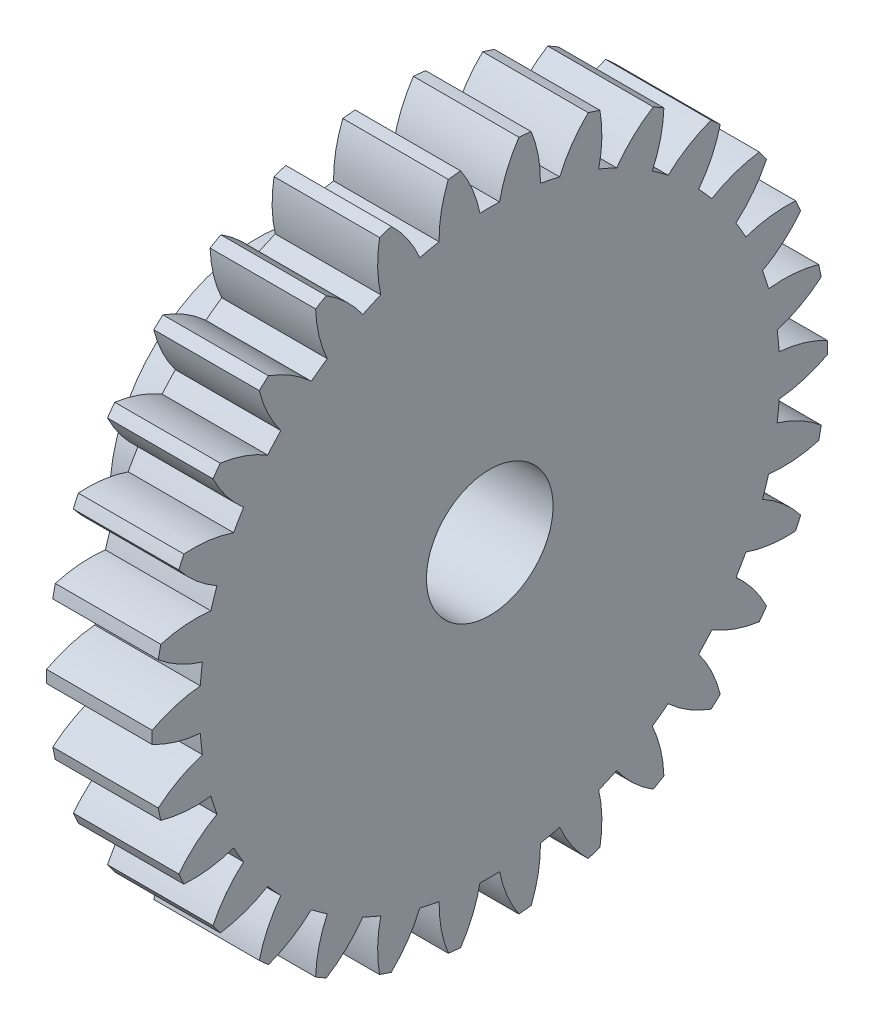
SolidWorks part; units mm, degrees
ref_plane "Plane1" through (0, 0, 0) normal (0, 0, 1) x (1, 0, 0)
ref_plane "Plane2" through (0, 0, 0) normal (0, 1, 0) x (1, 0, 0)
ref_plane "Plane3" through (0, 0, 0) normal (1, 0, 0) x (0, 0, -1)
sketch "HoldingSke" plane through (0, 0, 0) normal (0, 1, 0) x (1, 0, 0)
  line L0 (0, 0) -> (0.866, -0.5)
  line L1 (-15, 0) -> (100, 0) construction
  line L2 (0, 0) -> (-2.1039, 2.3779)
  line L3 (0, 0) -> (-11.863, 4.5341)
  line L4 (0, 0) -> (7.479, 4.318)
  line L5 (0, 0) -> (-10.3065, -3.844)
  line L6 (0, 0) -> (-4.1448, -2.7965)
  line L7 (-2.1039, 2.3779) -> (0.2639, 13.1201)
  line L8 (-76.2, 54.61) -> (-75.2, 54.61)
  line L9 (-71.009, 38.7566) -> (-53.1078, 45.2721)
  line L10 (-76.2, 71.12) -> (104.1128, 71.12)
  line L11 (0, 0) -> (-5, 0)
  line L12 (-76.2, 101.6) -> (-76.162, 101.6)
  line L13 (24.9733, 27.94) -> (52.9518, 28.4284)
  line L14 (24.9733, 27.94) -> (24.9743, 27.94)
  line L15 (24.9733, 27.94) -> (100.4006, 29.5858)
  line L16 (-63.627, -1) -> (-12.827, -1)
  circle A0 centre (0, 0) radius 3
  circle A1 centre (0, 0) radius 7
  circle A2 centre (0, 0) radius 7
  circle A3 centre (0, 0) radius 3
  dimension "Pitch" = 1
  dimension "Ap" = 20
  dimension "H" = 19.05
  dimension "Pitch_radius" = 180.3128
  dimension "Backlash" = 0.038
  dimension "Addendum_fac" = 1
  dimension "Dedendum_fac" = 1.25
  dimension "Clearance_fac" = 0.25
  dimension "Dedendum_add" = 0.001
  dimension "Module" = 1
sketch "BasProSke" plane through (0, 0, 0) normal (0, 1, 0) x (1, 0, 0)
  line L0 (-10, 0) -> (60, 0) construction
  line L1 (0, 0) -> (0, 16)
  line L2 (0, 0) -> (5, 0)
  line L3 (5, 0) -> (5, 16)
  line L4 (5, 16) -> (0, 16)
revolve "Base-Revolve" add sketch "BasProSke" angle 360 about L0
sketch "TooCutSke" plane through (0, 0, 0) normal (1, 0, 0) x (0, 0, -1)
  line L1 (0, 0) -> (0, 107) construction
  line L2 (0, 0) -> (-0.8515, 14.9758) construction
  line L3 (0, 0) -> (-3.1323, 29.8014) construction
  line L4 (-0.8515, 14.9758) -> (-1.5661, 14.9007) construction
  arc A0 (0.4664, 13.7411) -> (-0.4664, 13.7411) centre (0, 0) ccw
  arc A1 (1.3975, 15.9644) -> (-1.3975, 15.9644) centre (0, 0) ccw
  circle A2 centre (0, 0) radius 15 construction
  circle A3 centre (0, 0) radius 14.0954 construction
  arc A4 (-0.4664, 13.7411) -> (-1.3975, 15.9644) centre (-6.3534, 12.5823) ccw
  arc A5 (1.3975, 15.9644) -> (0.4664, 13.7411) centre (6.3534, 12.5823) ccw
  dimension "Half_CT" = 0.7185
extrude "ToothCut" cut sketch "TooCutSke" along normal through all
fillet "Breaks" [suppressed] radius 0.02
fillet "RootFillets" [suppressed] radius 0.251
pattern_circular "TeethCuts" count 30 every 12 about axis through (-10, 0, 0) along (1, 0, 0) of "ToothCut", "RootFillets", "Breaks"
sketch "HubNeaOneSke" plane through (0, 0, 0) normal (-1, 0, 0) x (0, 0, 1)
  circle A0 centre (0, 0) radius 7
extrude "HubNearOne" add sketch "HubNeaOneSke" along normal blind 6.0001
sketch "HubNeaBotSke" plane through (0, 0, 0) normal (-1, 0, 0) x (0, 0, 1)
  circle A0 centre (0, 0) radius 7
extrude "HubNearBoth" [suppressed] add sketch "HubNeaBotSke" along normal blind 3
ref_plane "FarPln" through (5, 0, 0) normal (1, 0, 0) x (0, 0, -1)
sketch "HubFarSke" plane through (5, 0, 0) normal (1, 0, 0) x (0, 0, -1)
  circle A0 centre (0, 0) radius 7
extrude "HubFar" [suppressed] add sketch "HubFarSke" along normal blind 3
sketch "BorSke" plane through (0, 0, 0) normal (1, 0, 0) x (0, 0, -1)
  circle A0 centre (0, 0) radius 3
extrude "Bore" cut sketch "BorSke" along normal mid plane 22.0001
sketch "KeySke" plane through (0, 0, 0) normal (1, 0, 0) x (0, 0, -1)
  line L0 (-1, 0) -> (-1, 4)
  line L1 (-1, 4) -> (1, 4)
  line L2 (1, 4) -> (1, 0)
  line L3 (0, 0) -> (0, 34) construction
  line L4 (-1, 0) -> (1, 0)
extrude "Keyway" [suppressed] cut sketch "KeySke" along normal mid plane 22.0001
pattern_circular "Keyway2" [suppressed] count 2 every 90 about axis through (-10, 0, 0) along (1, 0, 0)
equation "' \"Module@HoldingSke\" = 6.35"
equation "' \"Num_teeth@HoldingSke\" = 12"
equation "' \"Ap@HoldingSke\" =  20"
equation "' \"Ap@HoldingSke\" = 20"
equation "' \"Width@HoldingSke\" = 0.5 * 25.4"
equation "' \"Hub_dia@HoldingSke\"= 1 * 25.4"
equation "' \"Hub_dia@HoldingSke\" = 1 * 25.4"
equation "' \"Overall_len@HoldingSke\" = 1.0 * 25.4"
equation "' \"Bore@HoldingSke\" = 0.75 * 25.4"
equation "' \"T_dim@HoldingSke\" = 0.1 * 25.4"
equation "' \"Width@KeySke\" = 0.25 * 25.4"
equation "' \"Show_teeth@HoldingSke\" = 13"
equation "' \"Backlash@HoldingSke\" = 0.009 * 25.4"
equation "' \"Addendum_fac@HoldingSke\" = 1.0"
equation "' \"Dedendum_fac@HoldingSke\" = 1.25"
equation "' \"Dedendum_add@HoldingSke\" = 0.00005 * 25.4"
equation "' \"Clearance_fac@HoldingSke\" = 0.25"
equation "\"Pitch@HoldingSke\" = 1 / \"Module@HoldingSke\""
equation "\"Overcut_dia@TooCutSke\" = (\"Num_teeth@HoldingSke\" + 2 * \"Addendum_fac@HoldingSke\") / \"Pitch@HoldingSke\" + 0.002 * 25.4"
equation "\"Pitch_dia@TooCutSke\" = \"Num_teeth@HoldingSke\" / \"Pitch@HoldingSke\""
equation "\"Base_dia@TooCutSke\" = \"Num_teeth@HoldingSke\" / \"Pitch@HoldingSke\" * cos((\"Ap@HoldingSke\"  * 3.14159265 / 180))"
equation "\"Root_dia@TooCutSke\" = (\"Num_teeth@HoldingSke\" + 2) / \"Pitch@HoldingSke\" - 2 * (\"Addendum_fac@HoldingSke\" + \"Dedendum_fac@HoldingSke\") / \"Pitch@HoldingSke\" - \"Dedendum_add@HoldingSke\" * 2"
equation "\"Half_ang@TooCutSke\" = 180 / \"Num_teeth@HoldingSke\""
equation "\"Half_CT@TooCutSke\" = \"Num_teeth@HoldingSke\" / \"Pitch@HoldingSke\" * sin((3.14159265 / 2 / \"Num_teeth@HoldingSke\")) / 2 - 7 * \"Backlash@HoldingSke\" / 4"
equation "\"Flank_rad@TooCutSke\" = \"Num_teeth@HoldingSke\" / \"Pitch@HoldingSke\" / 5"
equation "\"Radius@RootFillets\" = \"Clearance_fac@HoldingSke\" / \"Pitch@HoldingSke\" + \"Dedendum_add@HoldingSke\""
equation "\"Break_rad@Breaks\" = 0.02 / \"Pitch@HoldingSke\""
equation "\"Thickness@HoldingSke\" = \"Width@HoldingSke\""
equation "\"OAL@HoldingSke\" = \"Thickness@HoldingSke\""
equation "\"MHD@HoldingSke\" = (\"Num_teeth@HoldingSke\" + 2) / \"Pitch@HoldingSke\" - 2 * (\"Addendum_fac@HoldingSke\" + \"Dedendum_fac@HoldingSke\")  / \"Pitch@HoldingSke\" - \"Dedendum_add@HoldingSke\" * 2"
equation "\"MBD@HoldingSke\" = (\"Num_teeth@HoldingSke\" + 2) / \"Pitch@HoldingSke\" - 2 * (\"Addendum_fac@HoldingSke\" + \"Dedendum_fac@HoldingSke\")  / \"Pitch@HoldingSke\" - \"Dedendum_add@HoldingSke\" * 2 - 0.002 * 25.4"
equation "\"MHD@HoldingSke\" = ((sgn( \"MHD@HoldingSke\" - \"Hub_dia@HoldingSke\" )-1)*( \"MHD@HoldingSke\" - \"Hub_dia@HoldingSke\" ))/-2+ \"Hub_dia@HoldingSke\""
equation "\"MBD@HoldingSke\" = ((sgn( \"MBD@HoldingSke\" - \"Bore@HoldingSke\" )-1)*( \"MBD@HoldingSke\" - \"Bore@HoldingSke\" ))/-2+ \"Bore@HoldingSke\""
equation "\"OAL@HoldingSke\" = ((sgn( \"OAL@HoldingSke\" - \"Overall_len@HoldingSke\" )+1)*( \"OAL@HoldingSke\" - \"Overall_len@HoldingSke\" ))/2 + \"Overall_len@HoldingSke\" + 0.000002 * 25.4"
equation "\"Num_teeth@TeethCuts\" = int( \"Show_teeth@HoldingSke\" ) + 1"
equation "\"Num_teeth@TeethCuts\" = ((sgn( \"Num_teeth@TeethCuts\" - \"Num_teeth@HoldingSke\" )-1)*( \"Num_teeth@TeethCuts\" - \"Num_teeth@HoldingSke\" ))/-2+ \"Num_teeth@HoldingSke\""
equation "\"Num_teeth@TeethCuts\" = ((sgn( \"Num_teeth@TeethCuts\" - 2.0)+1)*( \"Num_teeth@TeethCuts\" - 2.0))/2 +2.0"
equation "\"Angle@TeethCuts\" = 360.0 / \"Num_teeth@HoldingSke\""
equation "\"Diameter@BasProSke\" = (\"Num_teeth@HoldingSke\" + 2 * \"Addendum_fac@HoldingSke\") / \"Pitch@HoldingSke\""
equation "\"Thickness@BasProSke\"  = \"Thickness@HoldingSke\""
equation "' \"Fillet_rad@BasProSke\" =  \"Thickness@HoldingSke\" * 0.05"
equation "' \"Fillet_rad@BasProSke\" = \"Thickness@HoldingSke\" * 0.05"
equation "\"MHD@HoldingSke\" = ((sgn( \"MHD@HoldingSke\" - \"Root_dia@TooCutSke\" )-1)*( \"MHD@HoldingSke\" - \"Root_dia@TooCutSke\" ))/-2+ \"Root_dia@TooCutSke\""
equation "\"Diameter@HubNeaOneSke\" = \"MHD@HoldingSke\""
equation "\"Length@HubNearOne\" = \"OAL@HoldingSke\" - \"Thickness@BasProSke\""
equation "\"Diameter@HubNeaBotSke\" = \"MHD@HoldingSke\""
equation "\"Length@HubNearBoth\" = ( \"OAL@HoldingSke\" - \"Thickness@BasProSke\" ) / 2.0"
equation "\"Thickness@FarPln\" = \"Thickness@BasProSke\""
equation "\"Diameter@HubFarSke\" = \"MHD@HoldingSke\""
equation "\"Length@HubFar\" = ( \"OAL@HoldingSke\" - \"Thickness@BasProSke\" ) / 2.0"
equation "\"Diameter@BorSke\" = \"MBD@HoldingSke\""
equation "\"D1@Bore\" = \"OAL@HoldingSke\" * 2.0"
equation "\"D1@Keyway\" = \"OAL@HoldingSke\" * 2.0"
equation "\"Offset@KeySke\" = \"T_dim@HoldingSke\" + \"MBD@HoldingSke\" / 2.0"
